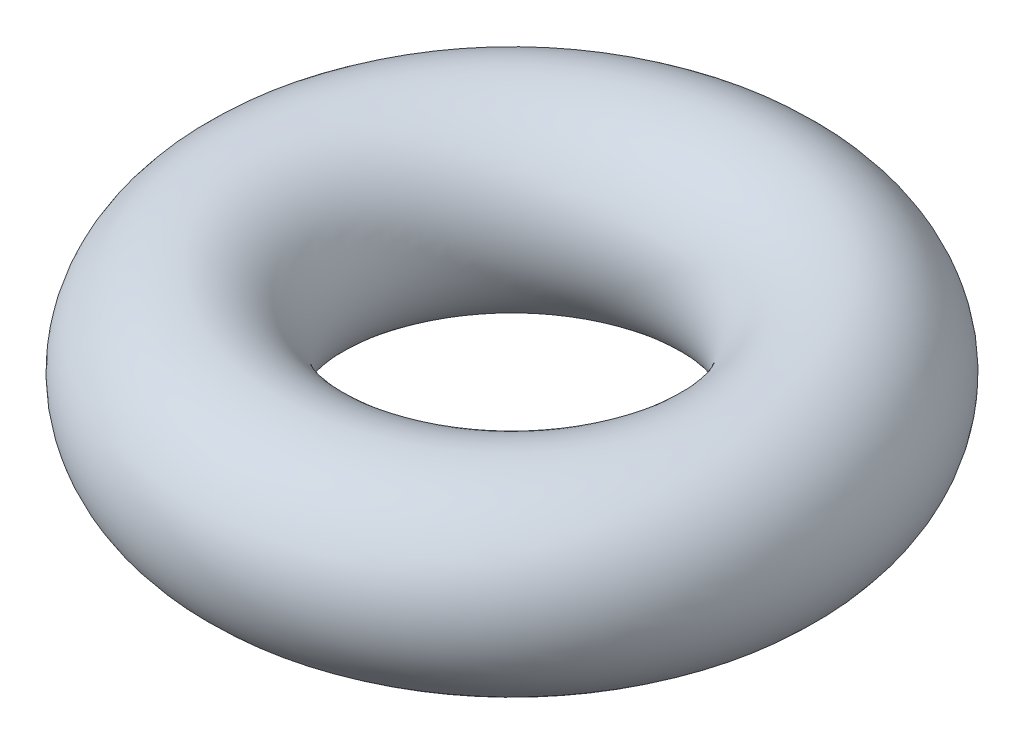
SolidWorks part; units mm, degrees
ref_plane "Front Plane" through (0, 0, 0) normal (0, 0, 1) x (1, 0, 0)
ref_plane "Top Plane" through (0, 0, 0) normal (0, 1, 0) x (1, 0, 0)
ref_plane "Right Plane" through (0, 0, 0) normal (1, 0, 0) x (0, 0, -1)
sketch "Sketch1" plane through (0, 0, 0) normal (0, 0, 1) x (1, 0, 0)
  line L0 (0, -3) -> (0, 3) construction
  circle A0 centre (5, 0) radius 2
revolve "Revolve1" add sketch "Sketch1" angle 360 about L0
